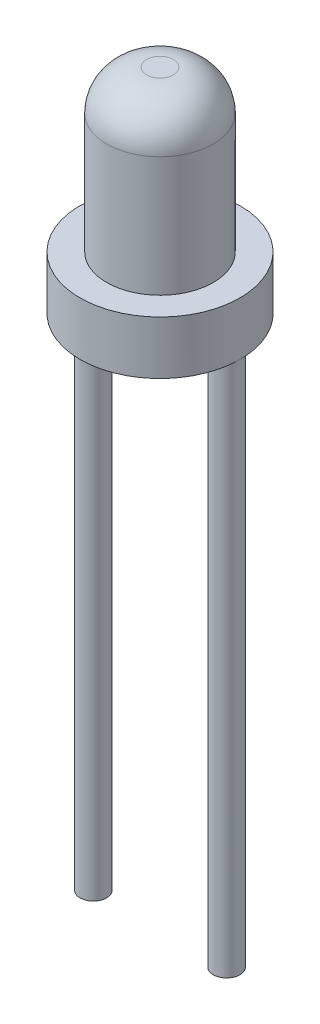
SolidWorks part; units mm, degrees
ref_plane "Plano frontal" through (0, 0, 0) normal (0, 0, 1) x (1, 0, 0)
ref_plane "Plano superior" through (0, 0, 0) normal (0, 1, 0) x (1, 0, 0)
ref_plane "Plano direito" through (0, 0, 0) normal (1, 0, 0) x (0, 0, -1)
sketch "Esboço1" plane through (0, 0, 0) normal (0, 0, 1) x (1, 0, 0)
  line L0 (0, 0) -> (0, 4) construction
  line L1 (0, 4) -> (0.25, 4)
  line L2 (1, 3.25) -> (1, 1)
  line L3 (1, 1) -> (1.5, 1)
  line L4 (1.5, 1) -> (1.5, 0)
  line L5 (1.5, 0) -> (0, 0)
  line L6 (0, 0) -> (0, 4)
  arc A0 (0.25, 4) -> (1, 3.25) centre (0.25, 3.25) cw
  dimension "D3" = 1.5
  dimension "D4" = 0.5
  dimension "D2" = 0.75
  dimension "D1" = 4
  dimension "D5" = 1
revolve "Revolução1" add sketch "Esboço1" angle 360 about L0
sketch "Esboço2" plane through (0, 0, 0) normal (0, -1, 0) x (1, 0, 0)
  line L0 (0, 1.5) -> (0, -1.5) construction
  line L1 (-1.25, 0) -> (0, 0) construction
  circle A0 centre (-1.25, 0) radius 0.25
  circle A1 centre (0, 0) radius 1.5 construction
  circle A2 centre (1.25, 0) radius 0.25
  dimension "D1" = 0.5
extrude "Ressalto-extrusão1" add sketch "Esboço2" along normal blind 10
